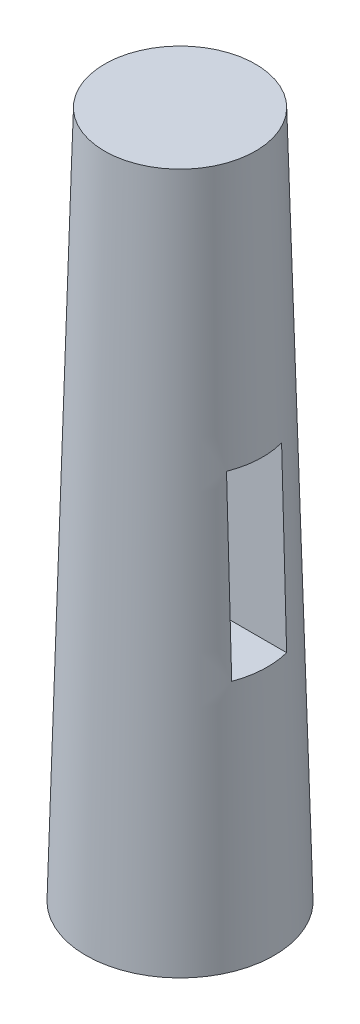
SolidWorks part; units mm, degrees
material "Plain Carbon Steel"
ref_plane "Front Plane" through (0, 0, 0) normal (0, 0, 1) x (1, 0, 0)
ref_plane "Top Plane" through (0, 0, 0) normal (0, 1, 0) x (1, 0, 0)
ref_plane "Right Plane" through (0, 0, 0) normal (1, 0, 0) x (0, 0, -1)
sketch "Sketch2" plane through (0, 0, 0) normal (0, 0, 1) x (1, 0, 0)
  line L0 (0, 86.7776) -> (0, -27.676) construction
  line L1 (0, 64.324) -> (10.1, 64.324)
  line L2 (0, -27.676) -> (12.6, -27.676)
  line L3 (0, 64.324) -> (0, -27.676)
  line L4 (10.1, 64.324) -> (12.6, -27.676)
  dimension "D1" = 10.1
  dimension "D2" = 12.6
  dimension "D3" = 92
revolve "Revolve1" add sketch "Sketch2" angle 360 about L0
sketch "Sketch3" plane through (0, 0, 0) normal (1, 0, 0) x (0, 0, -1)
  line L0 (-12.6, -27.676) -> (12.6, -27.676) construction
  line L1 (-4.0597, 29.324) -> (2.9403, 29.324)
  line L2 (-4.0597, 29.324) -> (-4.0597, 5.324)
  line L3 (-4.0597, 5.324) -> (2.9403, 5.324)
  line L4 (2.9403, 29.324) -> (2.9403, 5.324)
  line L5 (-4.0597, 29.324) -> (2.9403, 5.324) construction
  line L6 (-4.0597, 5.324) -> (2.9403, 29.324) construction
  point P0 (-0.5597, 17.324)
  dimension "D1" = 24
  dimension "D2" = 7
  dimension "D3" = 33
extrude "Cut-Extrude1" cut sketch "Sketch3" against normal through all both and the other way through all
